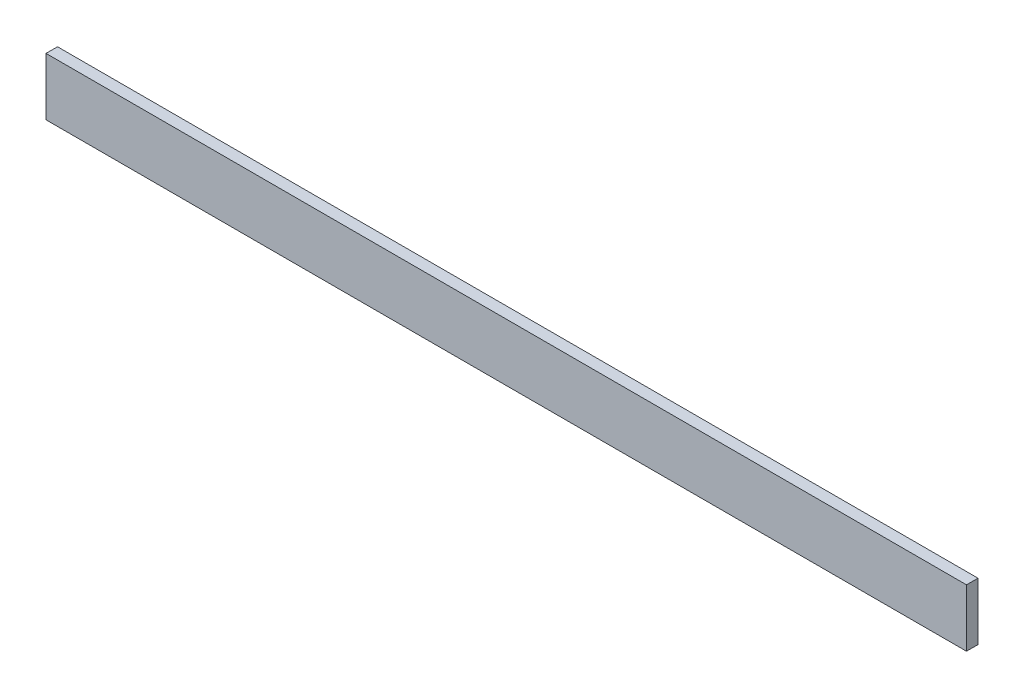
SolidWorks part; units mm, degrees
material "Akçaağaç"
ref_plane "Ön Düzlem" through (0, 0, 0) normal (0, 0, 1) x (1, 0, 0)
ref_plane "Üst Düzlem" through (0, 0, 0) normal (0, 1, 0) x (1, 0, 0)
ref_plane "Sağ Düzlem" through (0, 0, 0) normal (1, 0, 0) x (0, 0, -1)
sketch "Çizim1" plane through (0, 0, 0) normal (0, 0, 1) x (1, 0, 0)
  line L1 (400, -25) -> (-400, -25)
  line L2 (400, -25) -> (400, 25)
  line L3 (400, 25) -> (-400, 25)
  line L4 (-400, -25) -> (-400, 25)
  line L5 (400, -25) -> (-400, 25) construction
  line L6 (400, 25) -> (-400, -25) construction
  point P0 (0, 0)
  dimension "D1" = 50
  dimension "D2" = 800
extrude "Yükseklik-Ekstrüzyon1" add sketch "Çizim1" along normal blind 10
